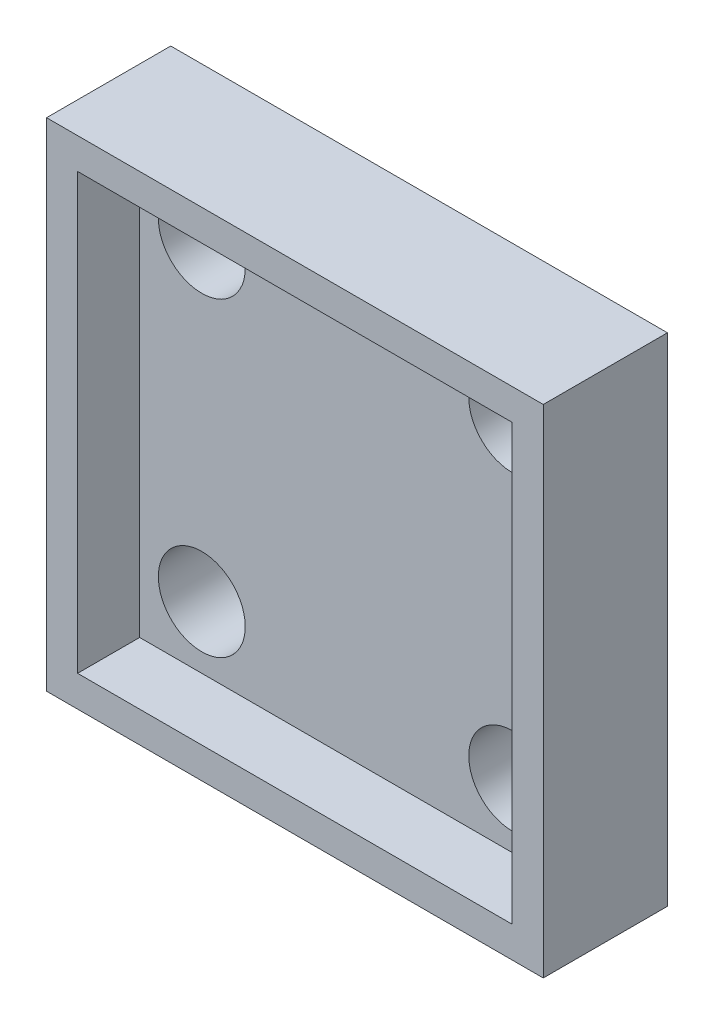
SolidWorks part; units mm, degrees
ref_plane "Alzado" through (0, 0, 0) normal (0, 0, 1) x (1, 0, 0)
ref_plane "Planta" through (0, 0, 0) normal (0, 1, 0) x (1, 0, 0)
ref_plane "Vista lateral" through (0, 0, 0) normal (1, 0, 0) x (0, 0, -1)
sketch "Croquis4" plane through (0, 0, 0) normal (0, 0, 1) x (1, 0, 0)
  line L1 (20, -20) -> (-20, -20)
  line L2 (20, -20) -> (20, 20)
  line L3 (20, 20) -> (-20, 20)
  line L4 (-20, -20) -> (-20, 20)
  line L5 (20, -20) -> (-20, 20) construction
  line L6 (20, 20) -> (-20, -20) construction
  point P0 (0, 0)
extrude "Saliente-Extruir7" add sketch "Croquis4" along normal blind 5
sketch "Croquis5" plane through (0, 0, 5) normal (0, 0, 1) x (1, 0, 0)
  line L1 (20, -20) -> (-20, -20)
  line L2 (20, -20) -> (20, 20)
  line L3 (20, 20) -> (-20, 20)
  line L4 (-20, -20) -> (-20, 20)
  line L5 (20, -20) -> (-20, 20) construction
  line L6 (20, 20) -> (-20, -20) construction
  line L7 (17.502, -17.502) -> (-17.502, -17.502)
  line L8 (17.502, -17.502) -> (17.502, 17.502)
  line L9 (17.502, 17.502) -> (-17.502, 17.502)
  line L10 (-17.502, -17.502) -> (-17.502, 17.502)
  line L11 (17.502, -17.502) -> (-17.502, 17.502) construction
  line L12 (17.502, 17.502) -> (-17.502, -17.502) construction
  point P0 (0, 0)
  point P6 (0, 0)
extrude "Saliente-Extruir8" add sketch "Croquis5" along normal blind 5
sketch "Croquis6" plane through (0, 0, 5) normal (0, 0, 1) x (1, 0, 0)
  circle A0 centre (-12.5, 12.5) radius 3.5
  circle A1 centre (12.5, 12.5) radius 3.5
  circle A2 centre (-12.5, -12.5) radius 3.5
  circle A3 centre (12.5, -12.5) radius 3.5
  point P0 (0, 0)
extrude "Cortar-Extruir1" cut sketch "Croquis6" against normal blind 13
